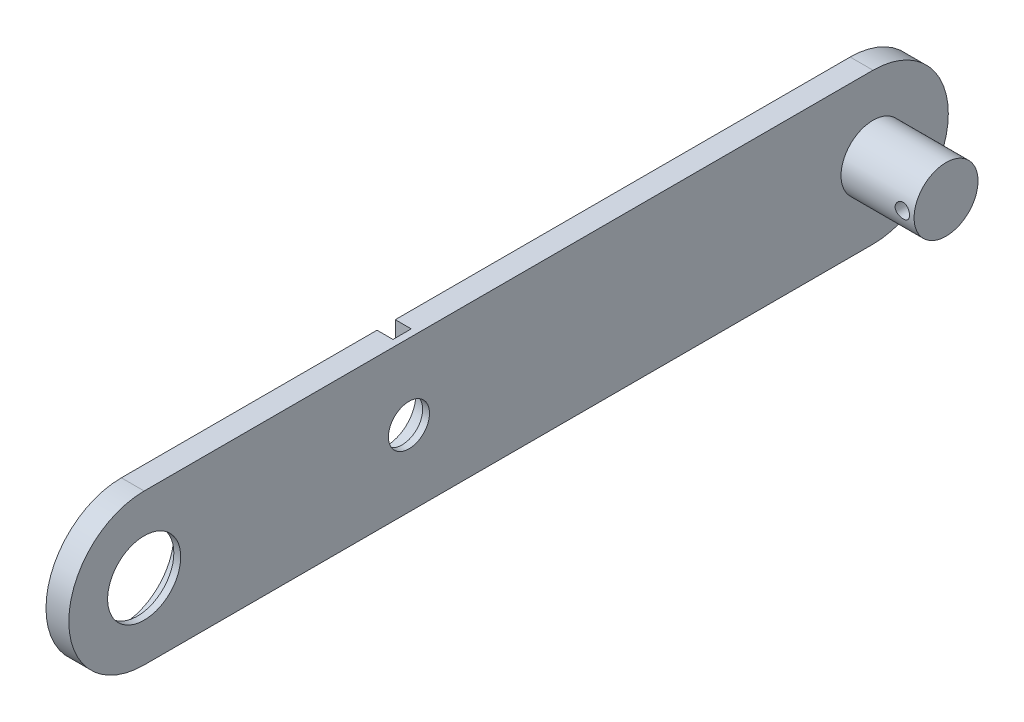
SolidWorks part; units mm, degrees
ref_plane "Front Plane" through (0, 0, 0) normal (0, 0, 1) x (1, 0, 0)
ref_plane "Top Plane" through (0, 0, 0) normal (0, 1, 0) x (1, 0, 0)
ref_plane "Right Plane" through (0, 0, 0) normal (1, 0, 0) x (0, 0, -1)
sketch "Sketch3" plane through (0, 20, 0) normal (-1, 0, 0) x (0, 1, 0)
  line L0 (-20, 101.629) -> (-20, -57.9977) construction
  line L3 (-3.5, 101.629) -> (-3.5, -57.9977)
  line L4 (-36.5, 101.629) -> (-36.5, -57.9977)
  line L5 (-20, 101.629) -> (31.303, -39.3249) construction
  line L6 (-20, -57.9977) -> (31.303, -39.3249) construction
  line L7 (-8.5, -57.9977) -> (-8.5, 0) construction
  line L9 (-8.5, 0) -> (10.1401, -51.2132) construction
  line L10 (10.1401, -51.2132) -> (-8.5, -57.9977) construction
  circle A4 centre (-20, 0) radius 6.5
  arc A8 (-3.5, 101.629) -> (-36.5, 101.629) centre (-20, 101.629) ccw
  arc A9 (-36.5, -57.9977) -> (-3.5, -57.9977) centre (-20, -57.9977) ccw
  circle A10 centre (-20, -57.9977) radius 11.5
  circle A11 centre (-20, 101.629) radius 11.5 construction
  point P6 (-20, 21.8156)
  dimension "D2" = 5
  dimension "D3" = 13
  dimension "D1" = 23
  dimension "D4" = 20
  dimension "D5" = 150
  dimension "D6" = 54.5
extrude "Boss-Extrude2" add sketch "Sketch3" along normal blind 3.5
sketch "Sketch4" plane through (0, 0, 0) normal (1, 0, 0) x (0, 0, -1)
  line L2 (101.629, 16.5) -> (-57.9977, 16.5)
  line L3 (-57.9977, -16.5) -> (101.629, -16.5)
  line L4 (101.629, 16.5) -> (-57.9977, 16.5)
  line L5 (-57.9977, -16.5) -> (101.629, -16.5)
  circle A0 centre (-57.9977, 0) radius 8
  arc A2 (101.629, -16.5) -> (101.629, 16.5) centre (101.629, 0) ccw
  arc A3 (-57.9977, 16.5) -> (-57.9977, -16.5) centre (-57.9977, 0) ccw
  arc A4 (101.629, -16.5) -> (101.629, 16.5) centre (101.629, 0) ccw
  arc A5 (-57.9977, 16.5) -> (-57.9977, -16.5) centre (-57.9977, 0) ccw
  circle A9 centre (0, 0) radius 4.5
  dimension "D2" = 16
  dimension "D3" = 9
  dimension "D1" = 0
extrude "Boss-Extrude3" add sketch "Sketch4" along normal blind 1.5
sketch "Sketch6" plane through (1.5, 0, 0) normal (1, 0, 0) x (0, 0, -1)
  circle A0 centre (101.629, 0) radius 7
  arc A1 (101.629, -16.5) -> (101.629, 16.5) centre (101.629, 0) ccw construction
  dimension "D1" = 7
extrude "Boss-Extrude4" add sketch "Sketch6" along normal blind 16
sketch "Sketch7" plane through (-3.5, 0, 0) normal (-1, 0, 0) x (0, 0, 1)
  line L0 (-2, 16.5) -> (-2, 6.1847)
  line L1 (57.9977, 16.5) -> (-101.629, 16.5) construction
  line L2 (-2, 16.5) -> (2, 16.5)
  line L3 (2, 16.5) -> (2, 6.1847)
  circle A0 centre (0, 0) radius 6.5 construction
  arc A1 (-2, 6.1847) -> (2, 6.1847) centre (0, 0) cw
  circle A2 centre (0, 0) radius 6.5 construction
  dimension "D1" = 4
extrude "Cut-Extrude1" cut sketch "Sketch7" against normal up to surface (3.5 mm away) up to face at (0, 0, -4.5)
ref_plane "Plane1" through (0, 0, -94.629) normal (0, 0, 1) x (1, 0, 0)
sketch "Sketch8" plane through (0, 0, -94.629) normal (0, 0, 1) x (1, 0, 0)
  line L0 (16.5, 0) -> (17.5, 0) construction
  line L1 (17.5, -7) -> (17.5, 7) construction
  line L2 (17.5, -7) -> (17.5, 7) construction
  circle A0 centre (14.925, 0) radius 1.575
  dimension "D1" = 3.15
  dimension "D2" = 1
extrude "Cut-Extrude2" cut sketch "Sketch8" against normal blind 3
ref_plane "Plane2" through (0, 0, -101.629) normal (0, 0, 1) x (1, 0, 0)
mirror "Mirror1" about plane through (0, 0, -101.629) normal (0, 0, 1) of "Cut-Extrude2"
